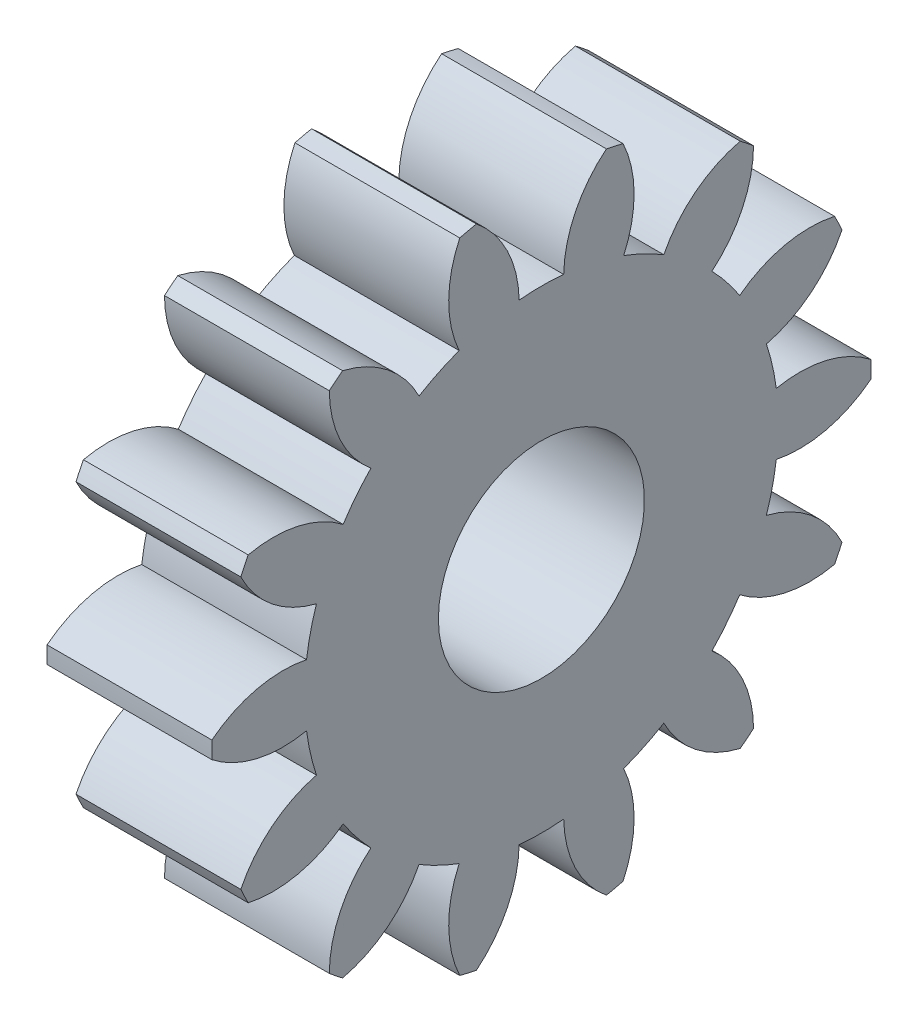
SolidWorks part; units mm, degrees
ref_plane "Plane1" through (0, 0, 0) normal (0, 0, 1) x (1, 0, 0)
ref_plane "Plane2" through (0, 0, 0) normal (0, 1, 0) x (1, 0, 0)
ref_plane "Plane3" through (0, 0, 0) normal (1, 0, 0) x (0, 0, -1)
sketch "HoldingSke" plane through (0, 0, 0) normal (0, 1, 0) x (1, 0, 0)
  line L0 (0, 0) -> (0.9703, -0.2419)
  line L1 (-15, 0) -> (100, 0) construction
  line L2 (0, 0) -> (-2.1039, 2.3779)
  line L3 (0, 0) -> (-11.863, 4.5341)
  line L4 (0, 0) -> (8.3795, 2.0892)
  line L5 (0, 0) -> (-46.8476, -17.4728)
  line L6 (0, 0) -> (-3.3159, -2.2372)
  line L7 (-2.1039, 2.3779) -> (8.6586, 51.2059)
  line L8 (-76.2, 54.61) -> (-75.3, 54.61)
  line L9 (-71.009, 38.7566) -> (-53.1078, 45.2721)
  line L10 (-76.2, 71.12) -> (104.1128, 71.12)
  line L11 (0, 0) -> (-4, 0)
  line L12 (-76.2, 101.6) -> (-76.162, 101.6)
  line L13 (24.9733, 27.94) -> (52.9518, 28.4284)
  line L14 (24.9733, 27.94) -> (24.9743, 27.94)
  line L15 (24.9733, 27.94) -> (100.4006, 29.5858)
  line L16 (-63.627, -1) -> (-12.827, -1)
  circle A0 centre (0, 0) radius 2.5
  circle A1 centre (0, 0) radius 5.749
  circle A2 centre (0, 0) radius 37.5
  circle A3 centre (0, 0) radius 2.5
  dimension "MHD" = 11.498
  dimension "Hub_dia" = 75
  dimension "Bore" = 5
  dimension "MBD" = 5
  dimension "Num_teeth" = 14
  dimension "Pitch" = 1
  dimension "Overall_len" = 50
  dimension "Show_teeth" = 14
  dimension "Thickness" = 4
  dimension "OAL" = 50.0001
  dimension "T_dim" = 0.9
  dimension "Ap" = 20
  dimension "H" = 19.05
  dimension "Pitch_radius" = 180.3128
  dimension "Width" = 4
  dimension "Backlash" = 0.038
  dimension "Addendum_fac" = 1
  dimension "Dedendum_fac" = 1.25
  dimension "Clearance_fac" = 0.25
  dimension "Dedendum_add" = 0.001
  dimension "Module" = 1
sketch "BasProSke" plane through (0, 0, 0) normal (0, 1, 0) x (1, 0, 0)
  line L0 (-10, 0) -> (60, 0) construction
  line L1 (0, 0) -> (0, 8)
  line L2 (0, 0) -> (4, 0)
  line L3 (4, 0) -> (4, 8)
  line L4 (4, 8) -> (0, 8)
  dimension "Thickness" = 4
  dimension "Diameter" = 16
revolve "Base-Revolve" add sketch "BasProSke" angle 360 about L0
sketch "TooCutSke" plane through (0, 0, 0) normal (1, 0, 0) x (0, 0, -1)
  line L1 (0, 0) -> (0, 107) construction
  line L2 (0, 0) -> (-0.8502, 6.9482) construction
  line L3 (0, 0) -> (-3.0989, 13.5772) construction
  line L4 (-0.8502, 6.9482) -> (-1.5494, 6.7886) construction
  arc A0 (0.5404, 5.7235) -> (-0.5404, 5.7235) centre (0, 0) ccw
  arc A1 (1.6036, 7.8636) -> (-1.6036, 7.8636) centre (0, 0) ccw
  circle A2 centre (0, 0) radius 7 construction
  circle A3 centre (0, 0) radius 6.5778 construction
  arc A4 (-0.5404, 5.7235) -> (-1.6036, 7.8636) centre (-3.3398, 5.6669) ccw
  arc A5 (1.6036, 7.8636) -> (0.5404, 5.7235) centre (3.3398, 5.6669) ccw
  dimension "Root_dia" = 11.498
  dimension "Overcut_dia" = 16.0508
  dimension "Pitch_dia" = 14
  dimension "Base_dia" = 13.1557
  dimension "Flank_rad" = 2.8
  dimension "Half_ang" = 12.857
  dimension "Half_CT" = 0.7173
extrude "ToothCut" cut sketch "TooCutSke" along normal through all
fillet "Breaks" [suppressed] radius 0.02
fillet "RootFillets" [suppressed] radius 0.251
pattern_circular "TeethCuts" count 14 every 25.714 about axis through (-10, 0, 0) along (1, 0, 0) of "ToothCut", "RootFillets", "Breaks"
sketch "HubNeaOneSke" plane through (0, 0, 0) normal (-1, 0, 0) x (0, 0, 1)
  circle A0 centre (0, 0) radius 5.749
  dimension "Diameter" = 11.498
extrude "HubNearOne" [suppressed] add sketch "HubNeaOneSke" along normal blind 46.0001
sketch "HubNeaBotSke" plane through (0, 0, 0) normal (-1, 0, 0) x (0, 0, 1)
  circle A0 centre (0, 0) radius 5.749
  dimension "Diameter" = 11.498
extrude "HubNearBoth" [suppressed] add sketch "HubNeaBotSke" along normal blind 23
ref_plane "FarPln" through (4, 0, 0) normal (1, 0, 0) x (0, 0, -1)
sketch "HubFarSke" plane through (4, 0, 0) normal (1, 0, 0) x (0, 0, -1)
  circle A0 centre (0, 0) radius 5.749
  dimension "Diameter" = 11.498
extrude "HubFar" [suppressed] add sketch "HubFarSke" along normal blind 23
sketch "BorSke" plane through (0, 0, 0) normal (1, 0, 0) x (0, 0, -1)
  circle A0 centre (0, 0) radius 2.5
  dimension "Diameter" = 5
extrude "Bore" cut sketch "BorSke" along normal mid plane 100.0001
sketch "KeySke" plane through (0, 0, 0) normal (1, 0, 0) x (0, 0, -1)
  line L0 (-1, 0) -> (-1, 3.4)
  line L1 (-1, 3.4) -> (1, 3.4)
  line L2 (1, 3.4) -> (1, 0)
  line L3 (0, 0) -> (0, 34) construction
  line L4 (-1, 0) -> (1, 0)
  dimension "Offset" = 3.4
  dimension "Width" = 2
extrude "Keyway" [suppressed] cut sketch "KeySke" along normal mid plane 100.0001
pattern_circular "Keyway2" [suppressed] count 2 every 90 about axis through (-10, 0, 0) along (1, 0, 0)
sketch "Sketch1" plane through (4, 0, 0) normal (1, 0, 0) x (0, 0, -1)
  circle A0 centre (0, 0) radius 8
equation "' \"Module@HoldingSke\" = 6.35"
equation "' \"Num_teeth@HoldingSke\" = 12"
equation "' \"Ap@HoldingSke\" =  20"
equation "' \"Ap@HoldingSke\" = 20"
equation "' \"Width@HoldingSke\" = 0.5 * 25.4"
equation "' \"Hub_dia@HoldingSke\"= 1 * 25.4"
equation "' \"Hub_dia@HoldingSke\" = 1 * 25.4"
equation "' \"Overall_len@HoldingSke\" = 1.0 * 25.4"
equation "' \"Bore@HoldingSke\" = 0.75 * 25.4"
equation "' \"T_dim@HoldingSke\" = 0.1 * 25.4"
equation "' \"Width@KeySke\" = 0.25 * 25.4"
equation "' \"Show_teeth@HoldingSke\" = 13"
equation "' \"Backlash@HoldingSke\" = 0.009 * 25.4"
equation "' \"Addendum_fac@HoldingSke\" = 1.0"
equation "' \"Dedendum_fac@HoldingSke\" = 1.25"
equation "' \"Dedendum_add@HoldingSke\" = 0.00005 * 25.4"
equation "' \"Clearance_fac@HoldingSke\" = 0.25"
equation "\"Pitch@HoldingSke\" = 1 / \"Module@HoldingSke\""
equation "\"Overcut_dia@TooCutSke\" = (\"Num_teeth@HoldingSke\" + 2 * \"Addendum_fac@HoldingSke\") / \"Pitch@HoldingSke\" + 0.002 * 25.4"
equation "\"Pitch_dia@TooCutSke\" = \"Num_teeth@HoldingSke\" / \"Pitch@HoldingSke\""
equation "\"Base_dia@TooCutSke\" = \"Num_teeth@HoldingSke\" / \"Pitch@HoldingSke\" * cos((\"Ap@HoldingSke\"  * 3.14159265 / 180))"
equation "\"Root_dia@TooCutSke\" = (\"Num_teeth@HoldingSke\" + 2) / \"Pitch@HoldingSke\" - 2 * (\"Addendum_fac@HoldingSke\" + \"Dedendum_fac@HoldingSke\") / \"Pitch@HoldingSke\" - \"Dedendum_add@HoldingSke\" * 2"
equation "\"Half_ang@TooCutSke\" = 180 / \"Num_teeth@HoldingSke\""
equation "\"Half_CT@TooCutSke\" = \"Num_teeth@HoldingSke\" / \"Pitch@HoldingSke\" * sin((3.14159265 / 2 / \"Num_teeth@HoldingSke\")) / 2 - 7 * \"Backlash@HoldingSke\" / 4"
equation "\"Flank_rad@TooCutSke\" = \"Num_teeth@HoldingSke\" / \"Pitch@HoldingSke\" / 5"
equation "\"Radius@RootFillets\" = \"Clearance_fac@HoldingSke\" / \"Pitch@HoldingSke\" + \"Dedendum_add@HoldingSke\""
equation "\"Break_rad@Breaks\" = 0.02 / \"Pitch@HoldingSke\""
equation "\"Thickness@HoldingSke\" = \"Width@HoldingSke\""
equation "\"OAL@HoldingSke\" = \"Thickness@HoldingSke\""
equation "\"MHD@HoldingSke\" = (\"Num_teeth@HoldingSke\" + 2) / \"Pitch@HoldingSke\" - 2 * (\"Addendum_fac@HoldingSke\" + \"Dedendum_fac@HoldingSke\")  / \"Pitch@HoldingSke\" - \"Dedendum_add@HoldingSke\" * 2"
equation "\"MBD@HoldingSke\" = (\"Num_teeth@HoldingSke\" + 2) / \"Pitch@HoldingSke\" - 2 * (\"Addendum_fac@HoldingSke\" + \"Dedendum_fac@HoldingSke\")  / \"Pitch@HoldingSke\" - \"Dedendum_add@HoldingSke\" * 2 - 0.002 * 25.4"
equation "\"MHD@HoldingSke\" = ((sgn( \"MHD@HoldingSke\" - \"Hub_dia@HoldingSke\" )-1)*( \"MHD@HoldingSke\" - \"Hub_dia@HoldingSke\" ))/-2+ \"Hub_dia@HoldingSke\""
equation "\"MBD@HoldingSke\" = ((sgn( \"MBD@HoldingSke\" - \"Bore@HoldingSke\" )-1)*( \"MBD@HoldingSke\" - \"Bore@HoldingSke\" ))/-2+ \"Bore@HoldingSke\""
equation "\"OAL@HoldingSke\" = ((sgn( \"OAL@HoldingSke\" - \"Overall_len@HoldingSke\" )+1)*( \"OAL@HoldingSke\" - \"Overall_len@HoldingSke\" ))/2 + \"Overall_len@HoldingSke\" + 0.000002 * 25.4"
equation "\"Num_teeth@TeethCuts\" = int( \"Show_teeth@HoldingSke\" ) + 1"
equation "\"Num_teeth@TeethCuts\" = ((sgn( \"Num_teeth@TeethCuts\" - \"Num_teeth@HoldingSke\" )-1)*( \"Num_teeth@TeethCuts\" - \"Num_teeth@HoldingSke\" ))/-2+ \"Num_teeth@HoldingSke\""
equation "\"Num_teeth@TeethCuts\" = ((sgn( \"Num_teeth@TeethCuts\" - 2.0)+1)*( \"Num_teeth@TeethCuts\" - 2.0))/2 +2.0"
equation "\"Angle@TeethCuts\" = 360.0 / \"Num_teeth@HoldingSke\""
equation "\"Diameter@BasProSke\" = (\"Num_teeth@HoldingSke\" + 2 * \"Addendum_fac@HoldingSke\") / \"Pitch@HoldingSke\""
equation "\"Thickness@BasProSke\"  = \"Thickness@HoldingSke\""
equation "' \"Fillet_rad@BasProSke\" =  \"Thickness@HoldingSke\" * 0.05"
equation "' \"Fillet_rad@BasProSke\" = \"Thickness@HoldingSke\" * 0.05"
equation "\"MHD@HoldingSke\" = ((sgn( \"MHD@HoldingSke\" - \"Root_dia@TooCutSke\" )-1)*( \"MHD@HoldingSke\" - \"Root_dia@TooCutSke\" ))/-2+ \"Root_dia@TooCutSke\""
equation "\"Diameter@HubNeaOneSke\" = \"MHD@HoldingSke\""
equation "\"Length@HubNearOne\" = \"OAL@HoldingSke\" - \"Thickness@BasProSke\""
equation "\"Diameter@HubNeaBotSke\" = \"MHD@HoldingSke\""
equation "\"Length@HubNearBoth\" = ( \"OAL@HoldingSke\" - \"Thickness@BasProSke\" ) / 2.0"
equation "\"Thickness@FarPln\" = \"Thickness@BasProSke\""
equation "\"Diameter@HubFarSke\" = \"MHD@HoldingSke\""
equation "\"Length@HubFar\" = ( \"OAL@HoldingSke\" - \"Thickness@BasProSke\" ) / 2.0"
equation "\"Diameter@BorSke\" = \"MBD@HoldingSke\""
equation "\"D1@Bore\" = \"OAL@HoldingSke\" * 2.0"
equation "\"D1@Keyway\" = \"OAL@HoldingSke\" * 2.0"
equation "\"Offset@KeySke\" = \"T_dim@HoldingSke\" + \"MBD@HoldingSke\" / 2.0"
